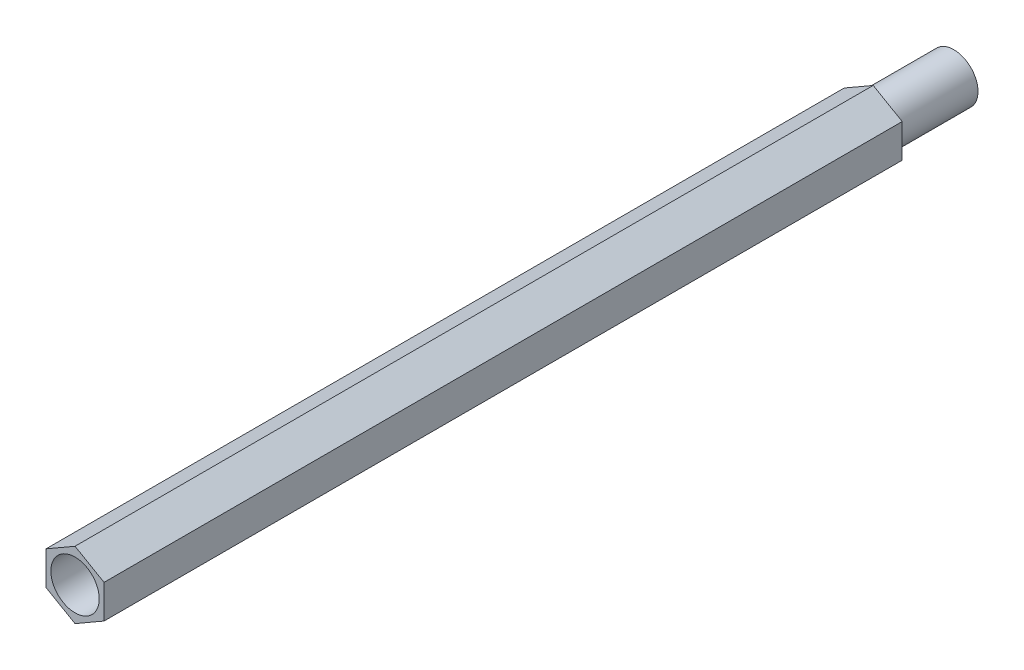
SolidWorks part; units mm, degrees
ref_plane "前视基准面" through (0, 0, 0) normal (0, 0, 1) x (1, 0, 0)
ref_plane "上视基准面" through (0, 0, 0) normal (0, 1, 0) x (1, 0, 0)
ref_plane "右视基准面" through (0, 0, 0) normal (1, 0, 0) x (0, 0, -1)
sketch "草图1" plane through (0, 0, 0) normal (0, 0, 1) x (1, 0, 0)
  line L1 (0, 2.0785) -> (-1.8, 1.0392)
  line L2 (-1.8, 1.0392) -> (-1.8, -1.0392)
  line L3 (-1.8, -1.0392) -> (0, -2.0785)
  line L4 (0, -2.0785) -> (1.8, -1.0392)
  line L5 (1.8, -1.0392) -> (1.8, 1.0392)
  line L6 (1.8, 1.0392) -> (0, 2.0785)
  circle A0 centre (0, 0) radius 1.8 construction
  circle A1 centre (0, 0) radius 1.5
extrude "凸台-拉伸1" add sketch "草图1" along normal blind 49.5
sketch "草图2" plane through (0, 0, 0) normal (0, 0, -1) x (-1, 0, 0)
  circle A0 centre (0, 0) radius 1.5
  circle A1 centre (0, 0) radius 1.5
  circle M8 centre (0, 0) radius 1.5
extrude "凸台-拉伸2" add sketch "草图2" along normal mid plane 10 contours M8
